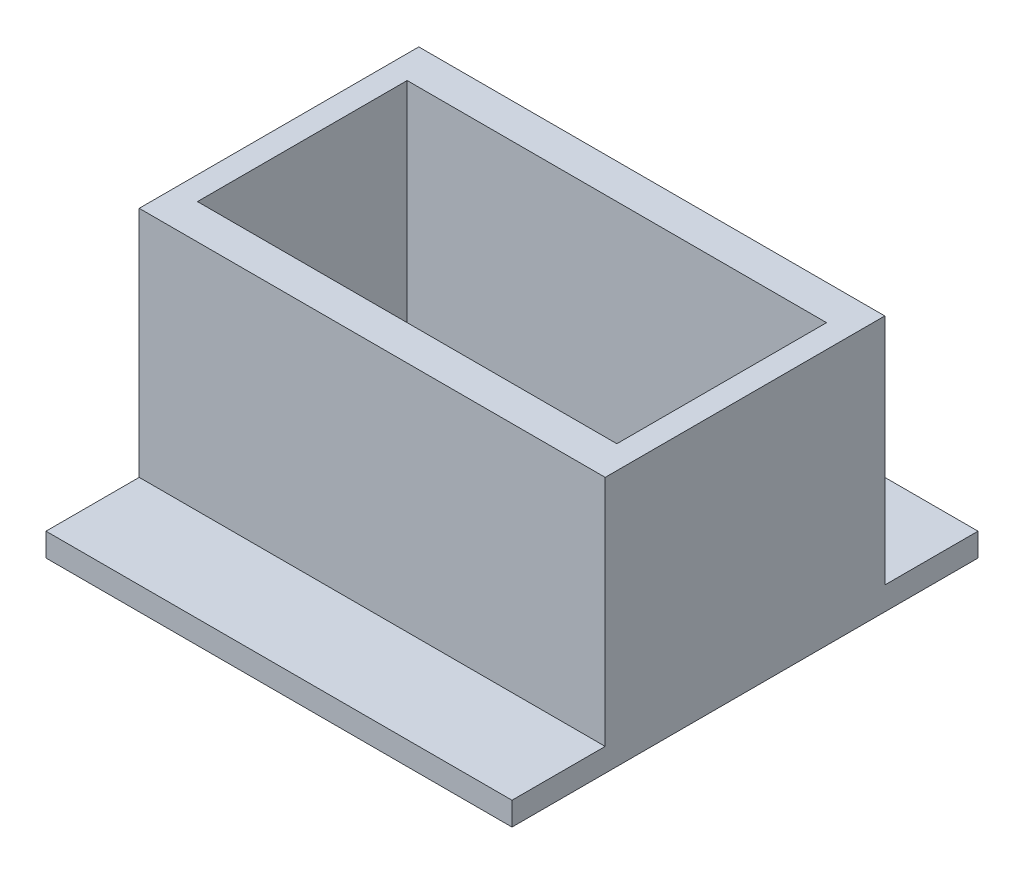
SolidWorks part; units mm, degrees
ref_plane "Front Plane" through (0, 0, 0) normal (0, 0, 1) x (1, 0, 0)
ref_plane "Top Plane" through (0, 0, 0) normal (0, 1, 0) x (1, 0, 0)
ref_plane "Right Plane" through (0, 0, 0) normal (1, 0, 0) x (0, 0, -1)
sketch "Sketch1" plane through (0, 0, 0) normal (0, 1, 0) x (1, 0, 0)
  line L1 (0, 0) -> (50.8, 0)
  line L2 (0, 0) -> (0, 50.8)
  line L3 (0, 50.8) -> (50.8, 50.8)
  line L4 (50.8, 0) -> (50.8, 50.8)
  dimension "D1" = 50.8
  dimension "D2" = 50.8
extrude "Boss-Extrude1" add sketch "Sketch1" along normal blind 2.54
sketch "Sketch2" plane through (0, 2.54, 0) normal (0, 1, 0) x (1, 0, 0)
  line L1 (0, 50.8) -> (50.8, 50.8)
  line L2 (0, 50.8) -> (0, 0)
  line L3 (0, 0) -> (50.8, 0)
  line L4 (50.8, 50.8) -> (50.8, 0)
  line L5 (2.54, 36.83) -> (48.26, 36.83)
  line L6 (2.54, 36.83) -> (2.54, 13.97)
  line L7 (2.54, 13.97) -> (48.26, 13.97)
  line L8 (48.26, 36.83) -> (48.26, 13.97)
  dimension "D1" = 22.86
  dimension "D2" = 45.72
  dimension "D3" = 2.54
  dimension "D4" = 13.97
extrude "Boss-Extrude2" add sketch "Sketch2" along normal blind 25.4
sketch "Sketch3" plane through (0, 27.94, 0) normal (0, 1, 0) x (1, 0, 0)
  line L0 (50.8, 0) -> (50.8, 50.8) construction
  line L1 (0, 50.8) -> (50.8, 50.8)
  line L2 (0, 50.8) -> (0, 40.64)
  line L3 (0, 40.64) -> (50.8, 40.64)
  line L4 (50.8, 50.8) -> (50.8, 40.64)
  line L5 (0, 50.8) -> (0, 0) construction
  line L6 (50.8, 0) -> (0, 0)
  line L7 (50.8, 0) -> (50.8, 10.16)
  line L8 (50.8, 10.16) -> (0, 10.16)
  line L9 (0, 0) -> (0, 10.16)
  dimension "D1" = 10.16
  dimension "D2" = 10.16
extrude "Cut-Extrude1" cut sketch "Sketch3" against normal blind 25.4
